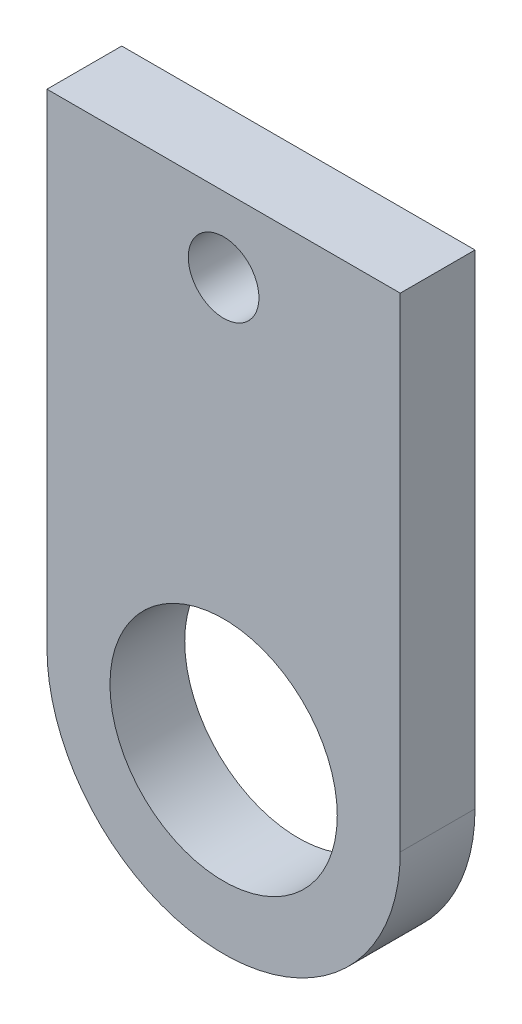
SolidWorks part; units mm, degrees
ref_plane "Front Plane" through (0, 0, 0) normal (0, 0, 1) x (1, 0, 0)
ref_plane "Top Plane" through (0, 0, 0) normal (0, 1, 0) x (1, 0, 0)
ref_plane "Right Plane" through (0, 0, 0) normal (1, 0, 0) x (0, 0, -1)
sketch "Sketch1" plane through (0, 0, 0) normal (0, 0, 1) x (1, 0, 0)
  line L0 (-69.3355, 27.1693) -> (-54.3355, 27.1693)
  line L1 (-69.3355, 27.1693) -> (-69.3355, 6.6193)
  line L2 (-54.3355, 27.1693) -> (-54.3355, 6.6193)
  line L3 (-61.8355, 25.6693) -> (-61.8355, -18.4551) construction
  arc A0 (-69.3355, 6.6193) -> (-54.3355, 6.6193) centre (-61.8355, 6.6193) ccw
  circle A1 centre (-61.8355, 6.6193) radius 4.826
  circle A2 centre (-61.8355, 23.9943) radius 1.5
  dimension "D1" = 7.5
  dimension "D3" = 9.652
  dimension "D5" = 3
  dimension "D2" = 20.55
  dimension "D4" = 3.175
extrude "Boss-Extrude1" add sketch "Sketch1" along normal blind 3.175
